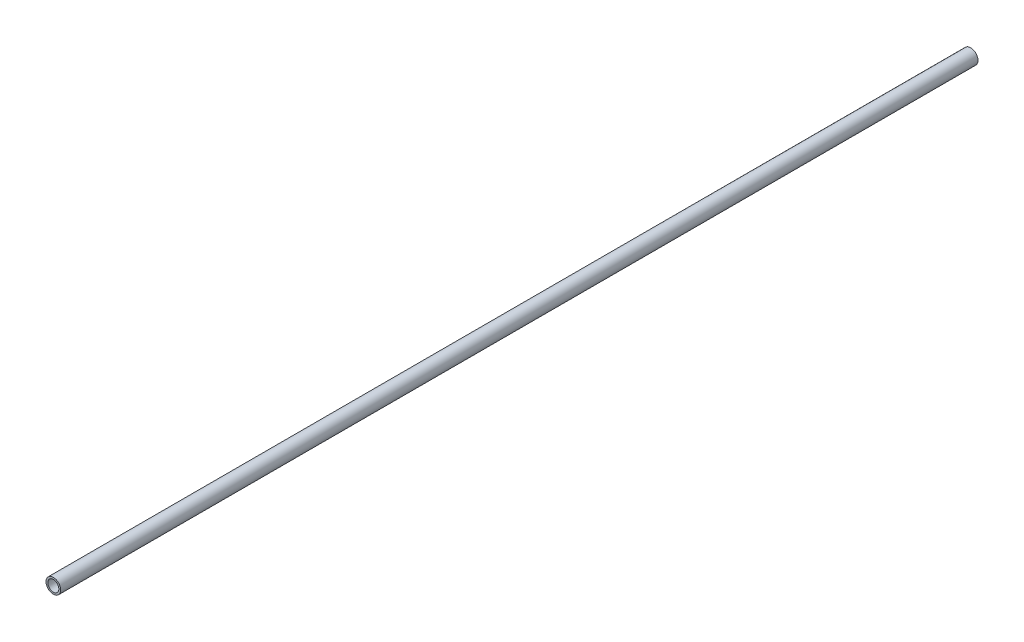
SolidWorks part; units mm, degrees
ref_plane "Front Plane" through (0, 0, 0) normal (0, 0, 1) x (1, 0, 0)
ref_plane "Top Plane" through (0, 0, 0) normal (0, 1, 0) x (1, 0, 0)
ref_plane "Right Plane" through (0, 0, 0) normal (1, 0, 0) x (0, 0, -1)
sketch "Sketch2" plane through (0, 0, 0) normal (0, 0, 1) x (1, 0, 0)
  circle A0 centre (0, 0) radius 4
  circle A1 centre (0, 0) radius 3
  dimension "D1" = 8
  dimension "D2" = 6
extrude "Boss-Extrude1" add sketch "Sketch2" along normal blind 500
